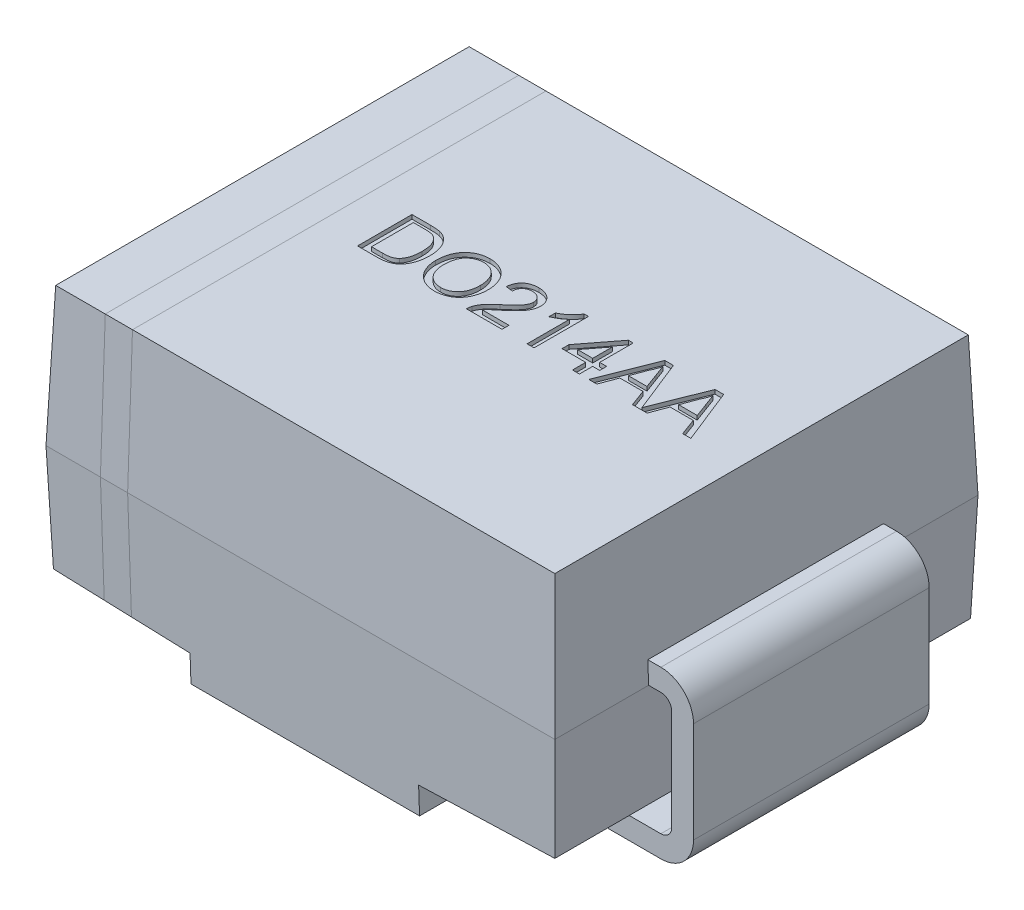
SolidWorks part; units mm, degrees
ref_plane "Front Plane" through (0, 0, 0) normal (0, 0, 1) x (1, 0, 0)
ref_plane "Top Plane" through (0, 0, 0) normal (0, 1, 0) x (1, 0, 0)
ref_plane "Right Plane" through (0, 0, 0) normal (1, 0, 0) x (0, 0, -1)
sketch "Sketch1" plane through (0, 0, 0) normal (0, 1, 0) x (1, 0, 0)
  line L0 (-3.1276, 0) -> (3.177, 0) construction
  line L1 (0, -2.6273) -> (0, 2.2408) construction
  line L3 (-2.3749, 1.9749) -> (2.3749, 1.9749)
  line L4 (-2.3749, 1.9749) -> (-2.3749, -1.9748)
  line L5 (-2.3749, -1.9748) -> (2.3749, -1.9748)
  line L6 (2.3749, 1.9749) -> (2.3749, -1.9748)
  dimension "D1" = 4.7498
  dimension "D2" = 3.9497
extrude "Extrude1" add sketch "Sketch1" along normal blind 1.2954 draft 2 and the other way blind 1.2954 draft 2
sketch "Sketch2" plane through (0, 0, 0) normal (0, 0, 1) x (1, 0, 0)
  line L0 (1.0668, -1.0414) -> (1.0668, -1.2954)
  line L1 (0, -1.7747) -> (0, 1.3591) construction
  line L2 (1.0668, -1.0414) -> (2.3401, -0.9969)
  line L3 (2.3297, -1.2954) -> (2.3749, 0) construction
  line L4 (-2.3297, -1.2954) -> (2.3297, -1.2954) construction
  line L5 (1.0668, -1.2954) -> (2.3297, -1.2954)
  line L6 (2.3401, -0.9969) -> (2.3297, -1.2954)
  line L7 (-1.0668, -1.0414) -> (-1.0668, -1.2954)
  line L8 (-1.0668, -1.0414) -> (-2.3401, -0.9969)
  line L9 (-2.3401, -0.9969) -> (-2.3297, -1.2954)
  line L10 (-1.0668, -1.2954) -> (-2.3297, -1.2954)
  dimension "D1" = 2.1336
  dimension "D2" = 2
  dimension "D3" = 0.254
  dimension "D4" = 0.2985
  dimension "D5" = 0.254
extrude "Cut-Extrude1" cut sketch "Sketch2" along normal up to surface and the other way up to surface
sketch "Sketch3" plane through (0, 0, 0) normal (0, 0, 1) x (1, 0, 0)
  line L0 (2.3678, 0.2032) -> (2.4892, 0.2032)
  line L1 (2.794, -0.1016) -> (2.794, -1.0414)
  line L2 (2.4892, -1.3462) -> (1.5367, -1.3462)
  line L3 (1.5367, -1.3462) -> (1.5367, -1.143)
  line L4 (1.5367, -1.143) -> (2.4892, -1.143)
  line L5 (2.5908, -1.0414) -> (2.5908, -0.1016)
  line L6 (2.4892, 0) -> (2.3749, 0)
  line L7 (2.3401, -0.9969) -> (2.3749, 0) construction
  line L8 (2.3678, 0.2032) -> (2.3749, 0)
  line L9 (-2.3297, 1.2954) -> (2.3297, 1.2954) construction
  line L10 (0, -2.4888) -> (0, 1.9414) construction
  line L11 (-2.3675, 0.2129) -> (-2.3749, 0)
  line L12 (-2.4892, 0) -> (-2.3749, 0)
  line L13 (-2.5908, -1.0414) -> (-2.5908, -0.1016)
  line L14 (-1.5367, -1.143) -> (-2.4892, -1.143)
  line L15 (-1.5367, -1.3462) -> (-1.5367, -1.143)
  line L16 (-2.4892, -1.3462) -> (-1.5367, -1.3462)
  line L17 (-2.794, -0.1016) -> (-2.794, -1.0414)
  line L18 (-2.3675, 0.2129) -> (-2.4892, 0.2032)
  line L19 (1.0668, -1.0414) -> (1.0668, -1.2954) construction
  line L20 (-2.3749, 0) -> (2.3749, 0) construction
  line L21 (2.3297, 1.2954) -> (2.3749, 0) construction
  line L22 (-2.3297, 1.2954) -> (-2.3749, 0) construction
  arc A0 (2.5908, -0.1016) -> (2.4892, 0) centre (2.4892, -0.1016) ccw
  arc A1 (2.4892, -1.143) -> (2.5908, -1.0414) centre (2.4892, -1.0414) ccw
  arc A2 (2.4892, 0.2032) -> (2.794, -0.1016) centre (2.4892, -0.1016) cw
  arc A3 (2.794, -1.0414) -> (2.4892, -1.3462) centre (2.4892, -1.0414) cw
  arc A4 (-2.794, -1.0414) -> (-2.4892, -1.3462) centre (-2.4892, -1.0414) ccw
  arc A5 (-2.4892, 0.2032) -> (-2.794, -0.1016) centre (-2.4892, -0.1016) ccw
  arc A6 (-2.4892, -1.143) -> (-2.5908, -1.0414) centre (-2.4892, -1.0414) cw
  arc A7 (-2.5908, -0.1016) -> (-2.4892, 0) centre (-2.4892, -0.1016) cw
  point P2 (1.0668, -1.1684)
  dimension "D7" = 0.1016
  dimension "D8" = 0.3048
  dimension "D1" = 0.2032
  dimension "D2" = 0.2032
  dimension "D3" = 0.2032
  dimension "D4" = 2.6416
  dimension "D5" = 5.588
  dimension "D6" = 2.794
  dimension "D9" = 0.4699
  dimension "D10" = 0.1143
  dimension "D11" = 0.9398
extrude "Extrude2" add sketch "Sketch3" along normal mid plane 2.1996
sketch "Sketch4" plane through (0, 0, 0) normal (0, 0, 1) x (1, 0, 0)
  line L0 (-2.3297, 1.2954) -> (2.3297, 1.2954) construction
  line L1 (-1.8669, 1.2954) -> (-1.6129, 1.2954)
  line L2 (-1.8669, 1.2954) -> (-1.8669, -1.0135)
  line L3 (-1.8669, -1.0135) -> (-1.6129, -1.0223)
  line L4 (-1.6129, 1.2954) -> (-1.6129, -1.0223)
  line L5 (-1.0668, -1.0414) -> (-2.3401, -0.9969) construction
  dimension "D1" = 0.508
  dimension "D2" = 0.254
split line "Split Line1"
sketch "Sketch5" plane through (0, 1.2954, 0) normal (0, 1, 0) x (1, 0, 0)
  text T0 "DO214AA" font "Arial" height 0.508
extrude "Cut-Extrude2" cut sketch "Sketch5" against normal blind 0.0381
